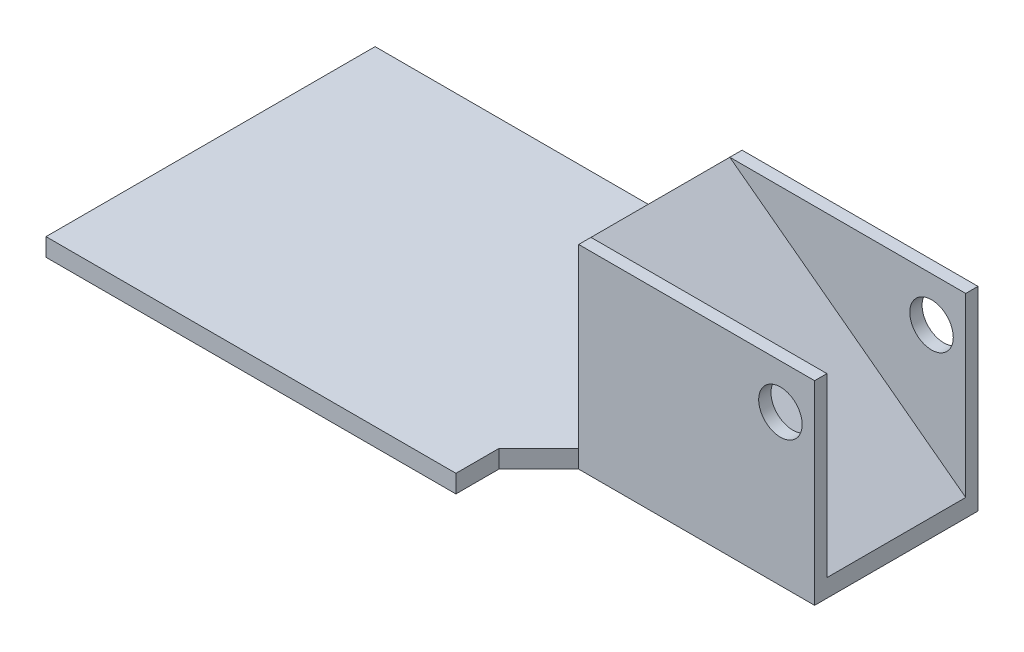
SolidWorks part; units mm, degrees
ref_plane "Front Plane" through (0, 0, 0) normal (0, 0, 1) x (1, 0, 0)
ref_plane "Top Plane" through (0, 0, 0) normal (0, 1, 0) x (1, 0, 0)
ref_plane "Right Plane" through (0, 0, 0) normal (1, 0, 0) x (0, 0, -1)
sketch "Sketch8" plane through (0, 0, 0) normal (0, 1, 0) x (1, 0, 0)
  line L0 (-44.9741, -2.9009) -> (-44.9741, -40.7469)
  line L1 (-44.9741, -40.7469) -> (2.1658, -40.7469)
  line L2 (2.1658, -40.7469) -> (2.1658, -35.808)
  line L3 (2.1658, -2.9009) -> (-44.9741, -2.9009)
  line L4 (2.1658, -7.8398) -> (6.7556, -12.4295)
  line L5 (2.1658, -7.8398) -> (2.1658, -2.9009)
  line L6 (6.7556, -31.2182) -> (2.1658, -35.808)
  line L7 (6.7556, -12.4295) -> (33.8879, -12.4295)
  line L8 (33.8879, -12.4295) -> (33.8879, -31.2182)
  line L9 (33.8879, -31.2182) -> (6.7556, -31.2182)
  line L10 (-44.9741, -21.8239) -> (33.8879, -21.8239) construction
  point P10 (0, 0)
  dimension "D1" = 37.846
  dimension "D2" = 47.1399
  dimension "D3" = 45
  dimension "D4" = 45
  dimension "D5" = 4.5898
  dimension "D6" = 18.923
  dimension "D7" = 4.9389
  dimension "D8" = 78.8619
extrude "Boss-Extrude6" add sketch "Sketch8" along normal blind 2.0599
sketch "Sketch9" plane through (0, 2.0599, 0) normal (0, 1, 0) x (1, 0, 0)
  line L0 (33.8879, -13.8418) -> (6.7556, -13.8418)
  line L1 (33.8879, -31.2182) -> (33.8879, -12.4295) construction
  line L2 (6.7556, -13.8418) -> (6.7556, -12.4295)
  line L3 (6.7556, -12.4295) -> (33.8879, -12.4295)
  line L4 (33.8879, -12.4295) -> (33.8879, -13.8418)
  line L5 (6.7556, -31.2182) -> (6.7556, -29.806)
  line L6 (6.7556, -29.806) -> (33.8879, -29.806)
  line L7 (33.8879, -29.806) -> (33.8879, -31.2182)
  line L8 (33.8879, -31.2182) -> (6.7556, -31.2182)
  dimension "D1" = 1.4122
  dimension "D2" = 1.4122
extrude "Boss-Extrude7" add sketch "Sketch9" along normal blind 20.32
sketch "Sketch10" plane through (0, 0, 31.2182) normal (0, 0, 1) x (1, 0, 0)
  line L0 (6.7556, 0) -> (33.8879, 0) construction
  line L1 (-44.9741, 2.0599) -> (-44.9741, 0) construction
  circle A0 centre (29.9559, 17.2847) radius 2.5006
  dimension "D2" = 74.93
  dimension "D1" = 17.2847
extrude "Cut-Extrude3" cut sketch "Sketch10" against normal blind 25.4
sketch "Sketch14" plane through (0, 0, 13.8418) normal (0, 0, 1) x (1, 0, 0)
  line L0 (6.7556, 22.3799) -> (33.8879, 2.0599)
  line L1 (6.7556, 22.3799) -> (6.7556, 19.8268)
  line L2 (6.7556, 22.3799) -> (6.7556, 2.0599) construction
  line L3 (6.7556, 19.8268) -> (30.5689, 2.0599)
  line L4 (30.5689, 2.0599) -> (33.8879, 2.0599)
extrude "Boss-Extrude10" add sketch "Sketch14" along normal blind 16.0299
